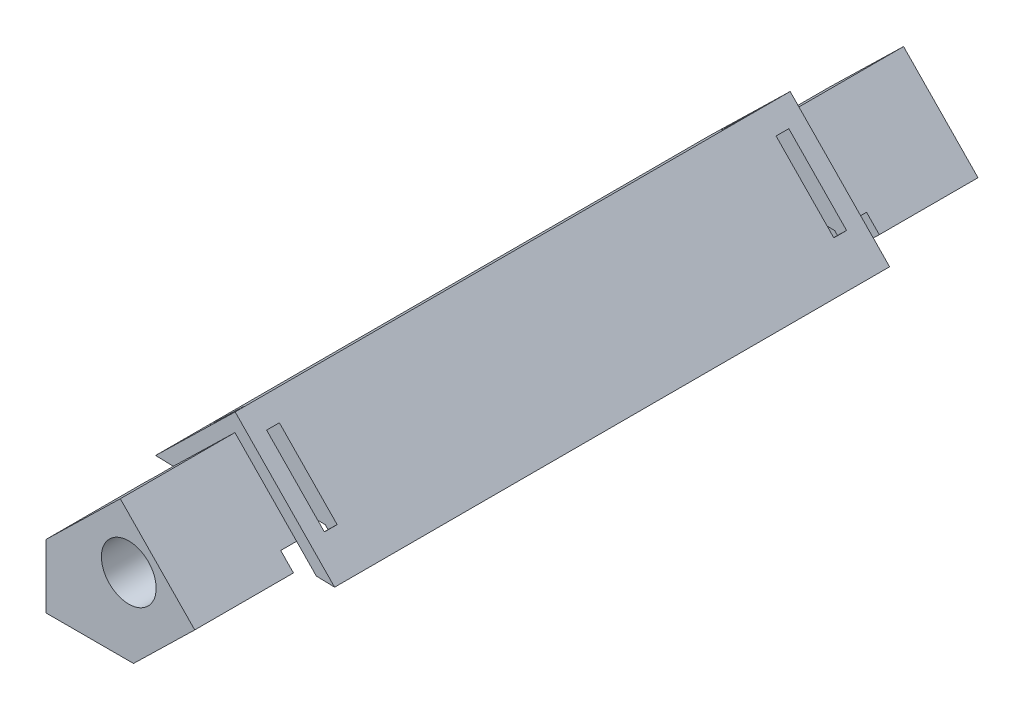
SolidWorks part; units mm, degrees
ref_plane "Plan de face" through (0, 0, 0) normal (0, 0, 1) x (1, 0, 0)
ref_plane "Plan de dessus" through (0, 0, 0) normal (0, 1, 0) x (1, 0, 0)
ref_plane "Plan de droite" through (0, 0, 0) normal (1, 0, 0) x (0, 0, -1)
sketch "Esquisse1" plane through (0, 0, 0) normal (0, 0, 1) x (1, 0, 0)
  line L0 (-29.2538, -8.8782) -> (-29.2538, -3.8788)
  line L5 (-22.3829, -8.8782) -> (-29.2538, -8.8782)
  line L6 (-23.4196, 1.8054) -> (-17.5747, -4.1937)
  line L7 (-17.5747, -4.1937) -> (-22.3829, -8.8782)
  line L8 (-23.4196, 1.8054) -> (-29.2538, -3.8788)
extrude "Boss.-Extru.1" add sketch "Esquisse1" along normal blind 61.5
hole_wizard "Dégagement M41" positions "Esquisse2" profile "Esquisse3" hole size "M4" standard "KS"
sketch "Esquisse2" plane through (0, 0, 61.5) normal (0, 0, 1) x (1, 0, 0)
  line L0 (-29.2538, -8.8782) -> (-22.3829, -8.8782) construction
  line L1 (-29.2538, -3.8788) -> (-29.2538, -8.8782) construction
  point P0 (-22.7538, -2.8782)
  dimension "D1" = 6
  dimension "D2" = 6.5
sketch "Esquisse3" plane through (-22.7538, -2.8782, 61.5) normal (1, 0, 0) x (0, -1, 0)
  line L0 (0, 0) -> (0, 7.2919)
  line L1 (0, 7.2919) -> (2.15, 6)
  line L2 (2.15, 6) -> (2.15, 0)
  line L5 (2.15, 0) -> (0, 0)
  line L10 (0, 7.2919) -> (-2.15, 6) construction
  line L11 (0, -6.35) -> (0, 107.95) construction
  dimension "Diamètre du perçage" = 4.3
  dimension "Profondeur du perçage" = 6
  dimension "Angle de pointe" = 118
hole_wizard "Dégagement M42" positions "Esquisse4" profile "Esquisse5" hole size "M4" standard "KS"
sketch "Esquisse4" plane through (0, 0, 0) normal (0, 0, -1) x (-1, 0, 0)
  line L0 (29.2538, -3.8788) -> (29.2538, -8.8782) construction
  line L1 (29.2538, -8.8782) -> (22.3829, -8.8782) construction
  point P0 (22.7538, -2.8782)
  dimension "D1" = 6.5
  dimension "D2" = 6
sketch "Esquisse5" plane through (-22.7538, -2.8782, 0) normal (1, 0, 0) x (0, 1, 0)
  line L0 (0, 0) -> (0, 7.2919)
  line L1 (0, 7.2919) -> (2.15, 6)
  line L2 (2.15, 6) -> (2.15, 0)
  line L5 (2.15, 0) -> (0, 0)
  line L10 (0, 7.2919) -> (-2.15, 6) construction
  line L11 (0, -6.35) -> (0, 107.95) construction
  dimension "Diamètre du perçage" = 4.3
  dimension "Profondeur du perçage" = 6
  dimension "Angle de pointe" = 118
ref_plane "Plan1" through (-23.4196, 1.8054, 61.5) normal (0, 0, -1) x (-1, 0, 0)
sketch "Esquisse9" plane through (-11.1124, -10.8266, 0) normal (0.7163, 0.6978, 0) x (0, 0, -1)
  line L0 (-61.5, 0.7237) -> (-61.5, 34.5487) construction
  line L1 (-51.25, 16.8862) -> (-50.25, 16.8862)
  line L2 (-51.25, 16.8862) -> (-51.25, 10.3862)
  line L3 (-51.25, 10.3862) -> (-50.25, 10.3862)
  line L4 (-50.25, 16.8862) -> (-50.25, 10.3862)
  line L5 (-11.25, 16.8862) -> (-10.25, 16.8862)
  line L6 (-11.25, 16.8862) -> (-11.25, 10.3862)
  line L7 (-11.25, 10.3862) -> (-10.25, 10.3862)
  line L8 (-10.25, 16.8862) -> (-10.25, 10.3862)
  line L12 (-61.5, 17.6362) -> (0, 17.6362) construction
  dimension "D1" = 6.5
  dimension "D2" = 1
  dimension "D3" = 6.5
  dimension "D4" = 1
  dimension "D5" = 39
  dimension "D6" = 10.25
  dimension "D7" = 0.75
  dimension "D8" = 0.75
extrude "Enlèv. mat.-Extru.2" cut sketch "Esquisse9" against normal through all
sketch "Esquisse11" plane through (-12.3071, 12.632, 0) normal (-0.6978, 0.7163, 0) x (0.7163, 0.6978, 0)
  line L0 (-15.5146, -61.5) -> (-15.5146, 0) construction
  line L1 (-19.2646, -50.25) -> (-16.2646, -50.25)
  line L2 (-19.2646, -50.25) -> (-19.2646, -51.25)
  line L3 (-19.2646, -51.25) -> (-16.2646, -51.25)
  line L4 (-16.2646, -50.25) -> (-16.2646, -51.25)
  line L5 (-19.2646, -10.25) -> (-16.2646, -10.25)
  line L6 (-19.2646, -10.25) -> (-19.2646, -11.25)
  line L7 (-19.2646, -11.25) -> (-16.2646, -11.25)
  line L8 (-16.2646, -10.25) -> (-16.2646, -11.25)
  line L9 (1.3979, -61.5) -> (-32.4271, -61.5) construction
  dimension "D1" = 39
  dimension "D2" = 3
  dimension "D3" = 3
  dimension "D4" = 1
  dimension "D5" = 1
  dimension "D6" = 0.75
  dimension "D7" = 0.75
  dimension "D8" = 10.25
extrude "Enlèv. mat.-Extru.3" cut sketch "Esquisse11" against normal blind 1
ref_plane "Plan9" through (0, 0, 30.75) normal (0, 0, -1) x (-1, 0, 0)
sketch "Esquisse14" plane through (0, 0, 30.75) normal (0, 0, -1) x (-1, 0, 0)
  line L0 (22.3829, -8.8782) -> (29.2538, -3.8788)
  line L3 (29.2538, -3.8788) -> (29.2538, -8.8782)
  line L4 (29.2538, -8.8782) -> (22.3829, -8.8782)
  line L5 (29.2538, -8.8782) -> (22.3829, -8.8782) construction
extrude "Enlèv. mat.-Extru.4" cut sketch "Esquisse14" against normal blind 23
sketch "Esquisse15" plane through (0, 0, 30.75) normal (0, 0, -1) x (-1, 0, 0)
  line L6 (17.5747, -4.1937) -> (22.3829, -8.8782)
  line L7 (22.3829, -8.8782) -> (29.2538, -3.8788)
  line L8 (29.2538, -3.8788) -> (17.5747, -4.1937)
extrude "Enlèv. mat.-Extru.7" cut sketch "Esquisse15" against normal blind 23
mirror "Symétrie2" about plane through (0, 0, 30.75) normal (0, 0, -1) of "Enlèv. mat.-Extru.7", "Enlèv. mat.-Extru.4"
sketch "Esquisse16" plane through (-12.3071, 12.632, 0) normal (-0.6978, 0.7163, 0) x (0.7163, 0.6978, 0)
  line L0 (-23.66, -53.75) -> (-23.66, -7.75) construction
  line L1 (-23.66, -9) -> (-15.5146, -9)
  line L2 (-23.66, -9) -> (-23.66, -52.5)
  line L3 (-23.66, -52.5) -> (-15.5146, -52.5)
  line L4 (-15.5146, -9) -> (-15.5146, -52.5)
  line L5 (-15.5146, -61.5) -> (-15.5146, 0) construction
  line L6 (-27.1488, -7.75) -> (-23.66, -7.75) construction
  line L7 (-19.2646, -10.25) -> (-16.2646, -10.25)
  line L8 (-19.2646, -10.25) -> (-19.2646, -11.25)
  line L9 (-19.2646, -11.25) -> (-16.2646, -11.25)
  line L10 (-16.2646, -10.25) -> (-16.2646, -11.25)
  line L11 (-19.2646, -50.25) -> (-16.2646, -50.25)
  line L12 (-19.2646, -50.25) -> (-19.2646, -51.25)
  line L13 (-19.2646, -51.25) -> (-16.2646, -51.25)
  line L14 (-16.2646, -50.25) -> (-16.2646, -51.25)
  line L15 (-27.1488, -53.75) -> (-23.66, -53.75) construction
  line L16 (-19.2646, -11.25) -> (-16.2646, -11.25) construction
  line L17 (-16.2646, -10.25) -> (-19.2646, -10.25) construction
  line L18 (-19.2646, -10.25) -> (-19.2646, -11.25) construction
  line L19 (-16.2646, -11.25) -> (-16.2646, -10.25) construction
  point P28 (-19.2646, -10.75)
  dimension "D1" = 1.25
  dimension "D2" = 1.25
extrude "Boss.-Extru.2" add sketch "Esquisse16" along normal blind 1
sketch "Esquisse17" plane through (-11.1124, -10.8266, 0) normal (0.7163, 0.6978, 0) x (0, 0, -1)
  line L0 (-53.75, 9.2605) -> (-7.75, 9.2605) construction
  line L1 (-52.5, 18.6362) -> (-8.9238, 18.6362)
  line L2 (-52.5, 18.6362) -> (-52.5, 9.2605)
  line L3 (-52.5, 9.2605) -> (-8.9238, 9.2605)
  line L4 (-8.9238, 18.6362) -> (-8.9238, 9.2605)
  line L6 (-51.25, 16.8862) -> (-50.25, 16.8862)
  line L7 (-51.25, 16.8862) -> (-51.25, 10.3862)
  line L8 (-51.25, 10.3862) -> (-50.25, 10.3862)
  line L9 (-50.25, 16.8862) -> (-50.25, 10.3862)
  line L10 (-11.25, 16.8862) -> (-10.25, 16.8862)
  line L11 (-11.25, 16.8862) -> (-11.25, 10.3862)
  line L12 (-11.25, 10.3862) -> (-10.25, 10.3862)
  line L13 (-10.25, 16.8862) -> (-10.25, 10.3862)
extrude "Boss.-Extru.3" add sketch "Esquisse17" along normal blind 1
sketch "Esquisse20" plane through (0, 0, 30.75) normal (0, 0, -1) x (-1, 0, 0)
  line L0 (30.4441, -5.0844) -> (23.5003, 1.8858)
  line L1 (23.5003, 1.8858) -> (17.2187, -4.5578)
  line L2 (17.2187, -4.5578) -> (30.4441, -5.0844)
extrude "Enlèv. mat.-Extru.9" [suppressed] cut sketch "Esquisse20" along normal up to vertex
sketch "Esquisse18" plane through (-0.1258, -4.6643, 0) normal (-0.027, -0.9996, 0) x (-0.9996, 0.027, 0)
  line L1 (31.1161, -53.75) -> (14.2239, -53.75)
  line L2 (31.1161, -53.75) -> (31.1161, -7.75)
  line L3 (31.1161, -7.75) -> (14.2239, -7.75)
  line L4 (14.2239, -53.75) -> (14.2239, -7.75)
extrude "Enlèv. mat.-Extru.8" cut sketch "Esquisse18" against normal blind 1
mirror "Symétrie3" [suppressed] about plane through (0, 0, 30.75) normal (0, 0, -1)
sketch "Esquisse21" plane through (0, 0, 52.5) normal (0, 0, 1) x (1, 0, 0)
  line L0 (-17.1419, -3.205) -> (-15.5915, -4.7963)
  line L1 (-15.5915, -4.7963) -> (-17.0253, -4.7577)
  line L2 (-17.0253, -4.7577) -> (-18.5757, -3.1664)
  line L3 (-17.5747, -4.1937) -> (-23.4196, 1.8054) construction
  line L4 (-18.5757, -3.1664) -> (-17.1419, -3.205)
  line L5 (-17.1419, -3.205) -> (-18.5757, -3.1664) construction
  line L6 (-23.4012, 3.2195) -> (-17.1419, -3.205) construction
extrude "Boss.-Extru.4" add sketch "Esquisse21" against normal up to vertex
sketch "Esquisse23" plane through (-10.3962, -10.1288, 0) normal (0.7163, 0.6978, 0) x (0, 0, -1)
  line L1 (-51.25, 16.8862) -> (-50.25, 16.8862)
  line L2 (-51.25, 16.8862) -> (-51.25, 10.3862)
  line L3 (-51.25, 10.3862) -> (-50.25, 10.3862)
  line L4 (-50.25, 16.8862) -> (-50.25, 10.3862)
  line L5 (-11.25, 16.8862) -> (-10.25, 16.8862)
  line L6 (-11.25, 16.8862) -> (-11.25, 10.3862)
  line L7 (-11.25, 10.3862) -> (-10.25, 10.3862)
  line L8 (-10.25, 16.8862) -> (-10.25, 10.3862)
extrude "Enlèv. mat.-Extru.11" cut sketch "Esquisse23" against normal through all
